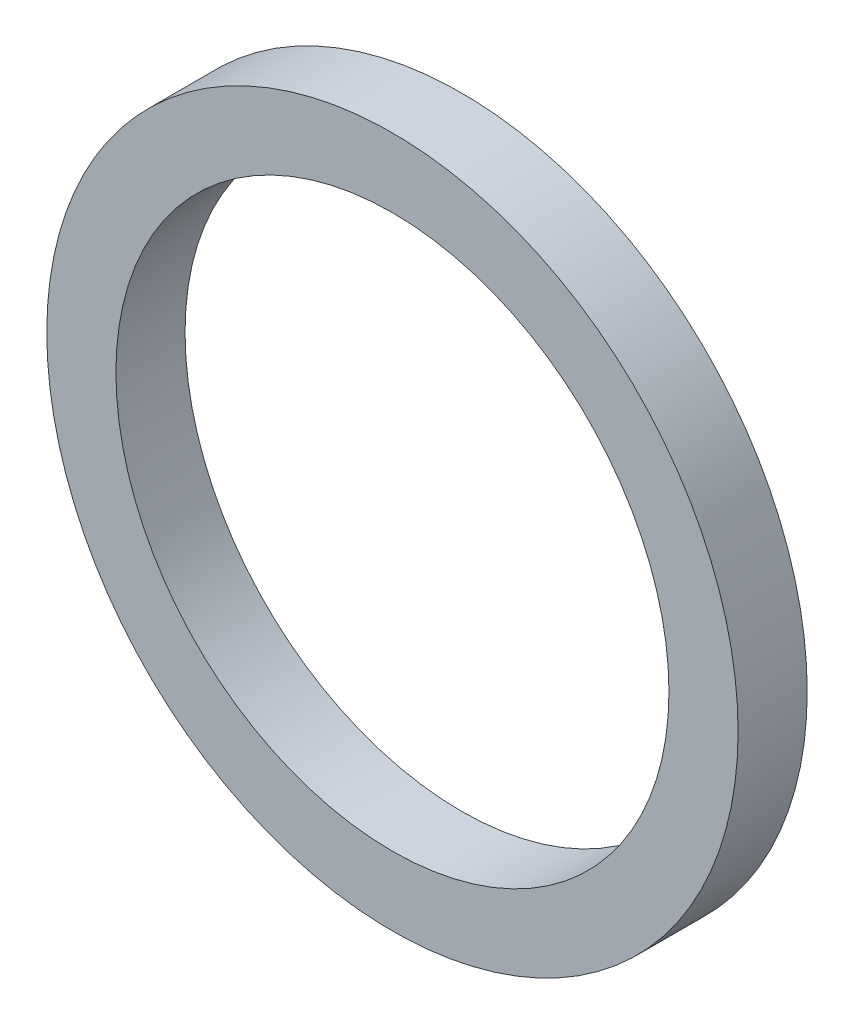
SolidWorks part; units mm, degrees
ref_plane "Front Plane" through (0, 0, 0) normal (0, 0, 1) x (1, 0, 0)
ref_plane "Top Plane" through (0, 0, 0) normal (0, 1, 0) x (1, 0, 0)
ref_plane "Right Plane" through (0, 0, 0) normal (1, 0, 0) x (0, 0, -1)
sketch "Sketch1" plane through (0, 0, 0) normal (0, 0, 1) x (1, 0, 0)
  circle A0 centre (0, 0) radius 7.9375
  circle A1 centre (0, 0) radius 6.35
  dimension "D1" = 12.7
  dimension "D2" = 15.875
extrude "Boss-Extrude1" add sketch "Sketch1" along normal blind 1.5875
